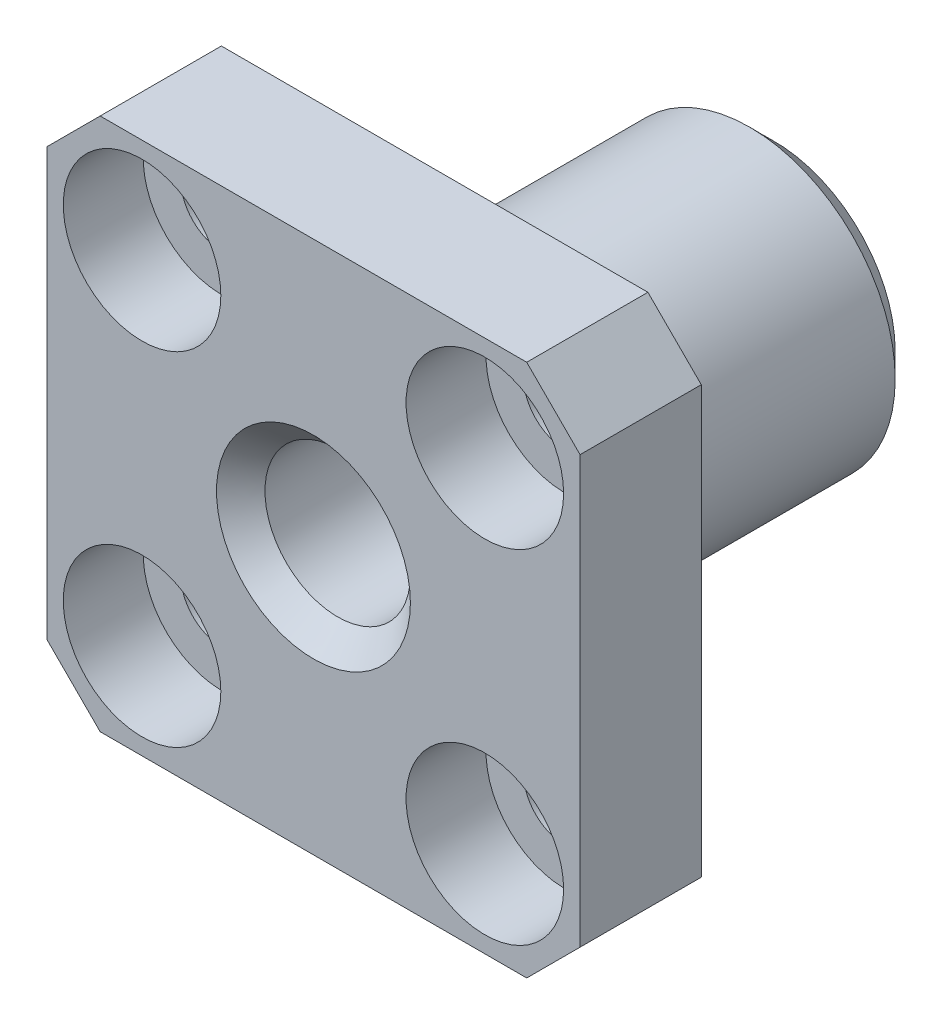
SolidWorks part; units mm, degrees
ref_plane "Front Plane" through (0, 0, 0) normal (0, 0, 1) x (1, 0, 0)
ref_plane "Top Plane" through (0, 0, 0) normal (0, 1, 0) x (1, 0, 0)
ref_plane "Right Plane" through (0, 0, 0) normal (1, 0, 0) x (0, 0, -1)
sketch "Sketch1" plane through (0, 0, 0) normal (0, 0, 1) x (1, 0, 0)
  circle A0 centre (0, 0) radius 6
  dimension "D1" = 12
extrude "Boss-Extrude1" add sketch "Sketch1" along normal blind 19
sketch "Sketch2" plane through (0, 0, 19) normal (0, 0, 1) x (1, 0, 0)
  line L1 (-11, -11) -> (11, -11)
  line L2 (-11, -11) -> (-11, 11)
  line L3 (-11, 11) -> (11, 11)
  line L4 (11, -11) -> (11, 11)
  line L5 (-11, -11) -> (11, 11) construction
  line L6 (-11, 11) -> (11, -11) construction
  point P0 (0, 0)
  dimension "D1" = 22
extrude "Boss-Extrude2" add sketch "Sketch2" against normal blind 5
sketch "Sketch4" plane through (0, 0, 19) normal (0, 0, 1) x (1, 0, 0)
  line L0 (0, 11) -> (0, -11) construction
  line L1 (11, 11) -> (-11, 11) construction
  line L2 (-11, -11) -> (11, -11) construction
  line L3 (-11, 11) -> (-11, 8.799)
  line L4 (-11, 11) -> (-11, -11) construction
  line L5 (-11, 8.799) -> (-8.799, 11)
  line L6 (-8.799, 11) -> (-11, 11)
  line L7 (8.799, 11) -> (11, 11)
  line L8 (11, 8.799) -> (8.799, 11)
  line L9 (11, 11) -> (11, 8.799)
  line L10 (-11, 0) -> (11, 0) construction
  line L11 (11, -11) -> (11, 11) construction
  line L12 (11, -11) -> (11, -8.799)
  line L13 (11, -8.799) -> (8.799, -11)
  line L14 (8.799, -11) -> (11, -11)
  line L15 (-8.799, -11) -> (-11, -11)
  line L16 (-11, -8.799) -> (-8.799, -11)
  line L17 (-11, -11) -> (-11, -8.799)
  point P25 (-11, 8.7729)
  point P26 (-8.8275, 11)
  dimension "D1" = 28
extrude "Cut-Extrude1" cut sketch "Sketch4" against normal through all
sketch "Sketch5" plane through (0, 0, 19) normal (0, 0, 1) x (1, 0, 0)
  line L0 (0, 0) -> (-9.8995, 9.8995) construction
  line L1 (-11, 8.799) -> (-8.799, 11) construction
  circle A0 centre (0, 0) radius 10 construction
  point P6 (-7.0711, 7.0711)
  point P7 (8.7817, 7.9638)
  point P8 (0, 0)
  point P10 (7.0711, 7.0711)
  point P11 (7.0711, -7.0711)
  point P12 (-7.0711, -7.0711)
  point P13 (0, 0)
  dimension "D1" = 20
  dimension "D2" = 4
hole_wizard "CBORE for M3 Hex Socket Head Cap Screw1" positions "Sketch6" profile "Sketch7" counterbore size "M3" standard "ISO"
sketch "Sketch6" plane through (0, 0, 19) normal (0, 0, 1) x (1, 0, 0)
  point P0 (-7.0711, 7.0711)
  point P3 (7.0711, 7.0711)
  point P6 (7.0711, -7.0711)
  point P9 (-7.0711, -7.0711)
sketch "Sketch7" plane through (-7.0711, 7.0711, 19) normal (1, 0, 0) x (0, -1, 0)
  line L0 (0, 0) -> (0, 23.0215)
  line L1 (0, 23.0215) -> (1.7, 22)
  line L2 (1.7, 22) -> (1.7, 3.3)
  line L3 (1.7, 3.3) -> (3.25, 3.3)
  line L4 (3.25, 3.3) -> (3.25, 0)
  line L5 (3.25, 0) -> (0, 0)
  line L10 (0, 23.0215) -> (-1.7, 22) construction
  line L11 (0, -6.35) -> (0, 107.95) construction
  dimension "Hole Dia." = 3.4
  dimension "Hole Depth" = 22
  dimension "C'Bore Dia." = 6.5
  dimension "C'Bore Depth" = 3.3
  dimension "Drill Angle" = 118
sketch "Sketch8" plane through (0, 0, 19) normal (0, 0, 1) x (1, 0, 0)
  circle A0 centre (0, 0) radius 3
  dimension "D1" = 6
extrude "Cut-Extrude2" cut sketch "Sketch8" against normal through all
chamfer "Chamfer1" distance 1 angle 45 2 edges at (6, 0, 0) (3, 0, 19)
